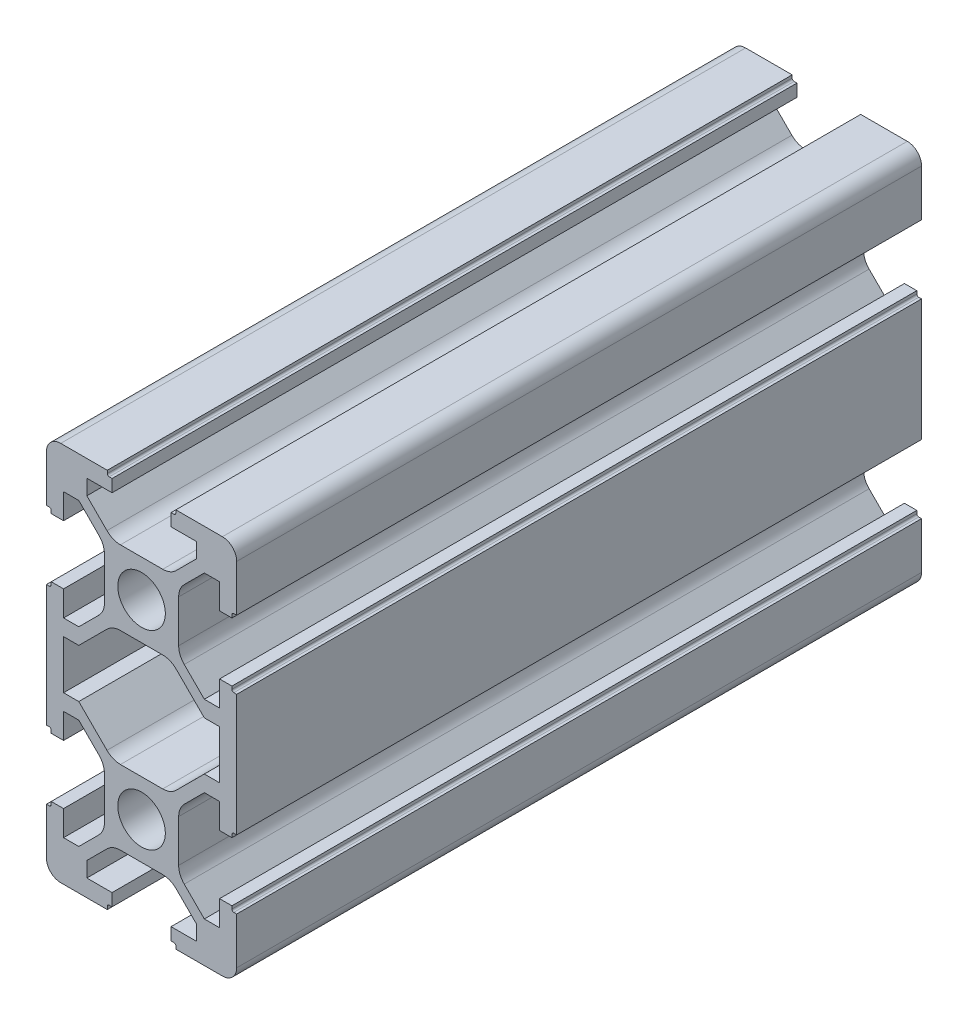
SolidWorks part; units mm, degrees
ref_plane "Alzado" through (0, 0, 0) normal (0, 0, 1) x (1, 0, 0)
ref_plane "Planta" through (0, 0, 0) normal (0, 1, 0) x (1, 0, 0)
ref_plane "Vista lateral" through (0, 0, 0) normal (1, 0, 0) x (0, 0, -1)
sketch "Croquis1" plane through (0, 0, 0) normal (0, 0, 1) x (1, 0, 0)
  line L0 (0, 0) -> (-10, -10) construction
  line L32 (0, 0) -> (-3.9, 0) construction
  line L58 (0, 0) -> (0, -3.9) construction
  line L60 (-4.4858, -3.6373) -> (-6.6, -5.7515)
  line L61 (-6.6, -5.7515) -> (-8.2, -5.7515)
  line L110 (-8.2, -5.7515) -> (-8.2, -3.1)
  line L111 (-8.2, -3.1) -> (-9.5, -3.1)
  line L112 (-9.5, -3.1) -> (-9.5, -3.4)
  line L113 (-9.7, -3.6) -> (-10, -3.6)
  line L114 (-10, -3.6) -> (-10, -8.5)
  line L115 (-3.6373, -4.4858) -> (-5.7515, -6.6)
  line L116 (-5.7515, -6.6) -> (-5.7515, -8.2)
  line L117 (-3.1, -8.2) -> (-3.1, -9.5)
  line L118 (-5.7515, -8.2) -> (-3.1, -8.2)
  line L119 (-3.1, -9.5) -> (-3.4, -9.5)
  line L120 (-3.6, -9.7) -> (-3.6, -10)
  line L121 (-3.6, -10) -> (-8.5, -10)
  line L122 (9.7, -3.6) -> (10, -3.6)
  line L123 (9.5, -3.1) -> (9.5, -3.4)
  line L124 (8.2, -3.1) -> (9.5, -3.1)
  line L125 (3.6, -10) -> (8.5, -10)
  line L126 (3.6, -9.7) -> (3.6, -10)
  line L127 (3.1, -9.5) -> (3.4, -9.5)
  line L128 (5.7515, -8.2) -> (3.1, -8.2)
  line L129 (3.1, -8.2) -> (3.1, -9.5)
  line L130 (5.7515, -6.6) -> (5.7515, -8.2)
  line L131 (3.6373, -4.4858) -> (5.7515, -6.6)
  line L132 (10, -3.6) -> (10, -8.5)
  line L133 (8.2, -5.7515) -> (8.2, -3.1)
  line L134 (6.6, -5.7515) -> (8.2, -5.7515)
  line L135 (4.4858, -3.6373) -> (6.6, -5.7515)
  line L136 (5.7515, 8.2) -> (3.1, 8.2)
  line L137 (3.6, 10) -> (8.5, 10)
  line L138 (-9.7, 3.6) -> (-10, 3.6)
  line L139 (-9.5, 3.1) -> (-9.5, 3.4)
  line L140 (-8.2, 3.1) -> (-9.5, 3.1)
  line L141 (-8.2, 5.7515) -> (-8.2, 3.1)
  line L142 (-6.6, 5.7515) -> (-8.2, 5.7515)
  line L143 (-4.4858, 3.6373) -> (-6.6, 5.7515)
  line L144 (3.1, 8.2) -> (3.1, 9.5)
  line L145 (3.1, 9.5) -> (3.4, 9.5)
  line L146 (3.6, 9.7) -> (3.6, 10)
  line L147 (-3.6, 10) -> (-8.5, 10)
  line L148 (-3.6, 9.7) -> (-3.6, 10)
  line L149 (-3.1, 9.5) -> (-3.4, 9.5)
  line L150 (-5.7515, 8.2) -> (-3.1, 8.2)
  line L151 (-3.1, 8.2) -> (-3.1, 9.5)
  line L152 (-5.7515, 6.6) -> (-5.7515, 8.2)
  line L153 (-3.6373, 4.4858) -> (-5.7515, 6.6)
  line L154 (-10, 3.6) -> (-10, 8.5)
  line L155 (4.4858, 3.6373) -> (6.6, 5.7515)
  line L156 (6.6, 5.7515) -> (8.2, 5.7515)
  line L157 (8.2, 5.7515) -> (8.2, 3.1)
  line L158 (10, 3.6) -> (10, 8.5)
  line L159 (3.6373, 4.4858) -> (5.7515, 6.6)
  line L160 (5.7515, 6.6) -> (5.7515, 8.2)
  line L161 (8.2, 3.1) -> (9.5, 3.1)
  line L162 (9.5, 3.1) -> (9.5, 3.4)
  line L163 (9.7, 3.6) -> (10, 3.6)
  line L164 (-3.9, 2.223) -> (-3.9, -2.223)
  line L165 (-2.223, -3.9) -> (2.223, -3.9)
  line L166 (3.9, -2.223) -> (3.9, 2.223)
  line L167 (2.223, 3.9) -> (-2.223, 3.9)
  circle A2 centre (0, 0) radius 2.5
  arc A3 (8.5, -10) -> (10, -8.5) centre (8.5, -8.5) ccw
  arc A4 (8.5, 10) -> (10, 8.5) centre (8.5, 8.5) cw
  arc A5 (-8.5, 10) -> (-10, 8.5) centre (-8.5, 8.5) ccw
  arc A6 (-10, -8.5) -> (-8.5, -10) centre (-8.5, -8.5) ccw
  arc A7 (-3.9, -2.223) -> (-4.4858, -3.6373) centre (-5.9, -2.223) cw
  arc A8 (4.4858, -3.6373) -> (3.9, -2.223) centre (5.9, -2.223) cw
  arc A9 (4.4858, 3.6373) -> (3.9, 2.223) centre (5.9, 2.223) ccw
  arc A10 (3.6373, 4.4858) -> (2.223, 3.9) centre (2.223, 5.9) cw
  arc A11 (-3.6373, 4.4858) -> (-2.223, 3.9) centre (-2.223, 5.9) ccw
  arc A12 (-4.4858, 3.6373) -> (-3.9, 2.223) centre (-5.9, 2.223) cw
  arc A13 (3.6373, -4.4858) -> (2.223, -3.9) centre (2.223, -5.9) ccw
  arc A14 (-3.6373, -4.4858) -> (-2.223, -3.9) centre (-2.223, -5.9) cw
  arc A15 (-3.4, -9.5) -> (-3.6, -9.7) centre (-3.4, -9.7) ccw
  arc A16 (3.6, -9.7) -> (3.4, -9.5) centre (3.4, -9.7) ccw
  arc A17 (9.7, -3.6) -> (9.5, -3.4) centre (9.7, -3.4) cw
  arc A18 (9.5, 3.4) -> (9.7, 3.6) centre (9.7, 3.4) cw
  arc A19 (3.4, 9.5) -> (3.6, 9.7) centre (3.4, 9.7) ccw
  arc A20 (-9.7, 3.6) -> (-9.5, 3.4) centre (-9.7, 3.4) cw
  arc A21 (-3.6, 9.7) -> (-3.4, 9.5) centre (-3.4, 9.7) ccw
  arc A22 (-9.5, -3.4) -> (-9.7, -3.6) centre (-9.7, -3.4) cw
  point P0 (0, 0)
  point P22 (10, -10)
  point P78 (10, 10)
  point P81 (-10, 10)
  point P90 (-3.9, -3.0515)
  point P93 (3.9, -3.0515)
  point P96 (3.9, 3.0515)
  point P99 (3.0515, 3.9)
  point P102 (-3.0515, 3.9)
  point P105 (-3.9, 3.0515)
  point P108 (3.0515, -3.9)
  point P111 (-3.0515, -3.9)
  point P116 (-3.6, -9.5)
  point P119 (3.6, -9.5)
  point P122 (9.5, -3.6)
  point P125 (9.5, 3.6)
  point P128 (3.6, 9.5)
  point P131 (-9.5, 3.6)
  point P134 (-3.6, 9.5)
  point P137 (-9.5, -3.6)
  dimension "D10" = 20
  dimension "D1" = 5
  dimension "D11" = 1.5
  dimension "D13" = 2
  dimension "D15" = 0.2
  dimension "D2" = 6.2
  dimension "D3" = 7.2
  dimension "D4" = 0.5
  dimension "D5" = 3.4
  dimension "D6" = 11.5029
  dimension "D7" = 6.1
  dimension "D8" = 1.8
  dimension "D9" = 1.2
extrude "Saliente-Extruir1" [suppressed] add sketch "Croquis1" along normal mid plane 100
sketch "Croquis3" plane through (0, 0, 0) normal (0, 0, 1) x (1, 0, 0)
  line L0 (-3.6363, -5.5152) -> (-6.6, -2.5556)
  line L3 (0, 0) -> (-10, 0) construction
  line L5 (-6.6, -2.5556) -> (-8.2, -2.5556)
  line L7 (0, -13.9) -> (0, -6.1) construction
  line L56 (-9.5, -13.1015) -> (-9.5, -13.4015)
  line L57 (-8.2, -13.1015) -> (-9.5, -13.1015)
  line L58 (-8.2, -15.7515) -> (-8.2, -13.1015)
  line L59 (-6.6, -15.7515) -> (-8.2, -15.7515)
  line L60 (-4.4858, -13.6373) -> (-6.6, -15.7515)
  line L61 (-3.9, -7.777) -> (-3.9, -12.223)
  line L62 (-6.6, -4.2515) -> (-4.4868, -6.3618)
  line L63 (-8.2, -4.2515) -> (-6.6, -4.2515)
  line L64 (-8.2, -6.9015) -> (-8.2, -4.2515)
  line L65 (-9.5, -6.9015) -> (-8.2, -6.9015)
  line L66 (-9.5, -6.6015) -> (-9.5, -6.9015)
  line L67 (-10, -6.4015) -> (-9.7, -6.4015)
  line L68 (-5.7515, -16.6) -> (-3.6373, -14.4858)
  line L69 (-5.7515, -18.2) -> (-5.7515, -16.6)
  line L70 (-3.1015, -18.2) -> (-5.7515, -18.2)
  line L71 (-3.1015, -19.5) -> (-3.1015, -18.2)
  line L72 (-3.4015, -19.5) -> (-3.1015, -19.5)
  line L73 (-3.6015, -20) -> (-3.6015, -19.7)
  line L74 (-8.5, -20) -> (-3.6015, -20)
  line L75 (-10, -13.6015) -> (-10, -18.5)
  line L76 (-9.7, -13.6015) -> (-10, -13.6015)
  line L102 (-10, -6.4015) -> (-10, 6.4015)
  line L103 (-8.2, -2.5556) -> (-8.2, 2.5556)
  line L104 (-2.223, -6.1) -> (2.223, -6.1)
  line L105 (-2.223, -13.9) -> (2.223, -13.9)
  line L106 (8.2, -2.5556) -> (8.2, 2.5556)
  line L107 (10, -6.4015) -> (10, 6.4015)
  line L108 (9.7, -13.6015) -> (10, -13.6015)
  line L109 (10, -13.6015) -> (10, -18.5)
  line L110 (8.5, -20) -> (3.6015, -20)
  line L111 (3.6015, -20) -> (3.6015, -19.7)
  line L112 (3.4015, -19.5) -> (3.1015, -19.5)
  line L113 (3.1015, -19.5) -> (3.1015, -18.2)
  line L114 (3.1015, -18.2) -> (5.7515, -18.2)
  line L115 (5.7515, -18.2) -> (5.7515, -16.6)
  line L116 (5.7515, -16.6) -> (3.6373, -14.4858)
  line L117 (10, -6.4015) -> (9.7, -6.4015)
  line L118 (9.5, -6.6015) -> (9.5, -6.9015)
  line L119 (9.5, -6.9015) -> (8.2, -6.9015)
  line L120 (8.2, -6.9015) -> (8.2, -4.2515)
  line L121 (8.2, -4.2515) -> (6.6, -4.2515)
  line L122 (6.6, -4.2515) -> (4.4868, -6.3618)
  line L123 (3.9, -7.777) -> (3.9, -12.223)
  line L124 (4.4858, -13.6373) -> (6.6, -15.7515)
  line L125 (6.6, -15.7515) -> (8.2, -15.7515)
  line L126 (8.2, -15.7515) -> (8.2, -13.1015)
  line L127 (8.2, -13.1015) -> (9.5, -13.1015)
  line L128 (9.5, -13.1015) -> (9.5, -13.4015)
  line L129 (6.6, -2.5556) -> (8.2, -2.5556)
  line L130 (3.6363, -5.5152) -> (6.6, -2.5556)
  line L131 (3.6363, 5.5152) -> (6.6, 2.5556)
  line L132 (6.6, 2.5556) -> (8.2, 2.5556)
  line L133 (9.5, 13.1015) -> (9.5, 13.4015)
  line L134 (8.2, 13.1015) -> (9.5, 13.1015)
  line L135 (8.2, 15.7515) -> (8.2, 13.1015)
  line L136 (6.6, 15.7515) -> (8.2, 15.7515)
  line L137 (4.4858, 13.6373) -> (6.6, 15.7515)
  line L138 (3.9, 7.777) -> (3.9, 12.223)
  line L139 (6.6, 4.2515) -> (4.4868, 6.3618)
  line L140 (8.2, 4.2515) -> (6.6, 4.2515)
  line L141 (8.2, 6.9015) -> (8.2, 4.2515)
  line L142 (9.5, 6.9015) -> (8.2, 6.9015)
  line L143 (9.5, 6.6015) -> (9.5, 6.9015)
  line L144 (10, 6.4015) -> (9.7, 6.4015)
  line L145 (5.7515, 16.6) -> (3.6373, 14.4858)
  line L146 (5.7515, 18.2) -> (5.7515, 16.6)
  line L147 (3.1015, 18.2) -> (5.7515, 18.2)
  line L148 (3.1015, 19.5) -> (3.1015, 18.2)
  line L149 (3.4015, 19.5) -> (3.1015, 19.5)
  line L150 (3.6015, 20) -> (3.6015, 19.7)
  line L151 (8.5, 20) -> (3.6015, 20)
  line L152 (10, 13.6015) -> (10, 18.5)
  line L153 (9.7, 13.6015) -> (10, 13.6015)
  line L154 (-2.223, 13.9) -> (2.223, 13.9)
  line L155 (-2.223, 6.1) -> (2.223, 6.1)
  line L156 (-9.7, 13.6015) -> (-10, 13.6015)
  line L157 (-10, 13.6015) -> (-10, 18.5)
  line L158 (-8.5, 20) -> (-3.6015, 20)
  line L159 (-3.6015, 20) -> (-3.6015, 19.7)
  line L160 (-3.4015, 19.5) -> (-3.1015, 19.5)
  line L161 (-3.1015, 19.5) -> (-3.1015, 18.2)
  line L162 (-3.1015, 18.2) -> (-5.7515, 18.2)
  line L163 (-5.7515, 18.2) -> (-5.7515, 16.6)
  line L164 (-5.7515, 16.6) -> (-3.6373, 14.4858)
  line L165 (-10, 6.4015) -> (-9.7, 6.4015)
  line L166 (-9.5, 6.6015) -> (-9.5, 6.9015)
  line L167 (-9.5, 6.9015) -> (-8.2, 6.9015)
  line L168 (-8.2, 6.9015) -> (-8.2, 4.2515)
  line L169 (-8.2, 4.2515) -> (-6.6, 4.2515)
  line L170 (-6.6, 4.2515) -> (-4.4868, 6.3618)
  line L171 (-3.9, 7.777) -> (-3.9, 12.223)
  line L172 (-4.4858, 13.6373) -> (-6.6, 15.7515)
  line L173 (-6.6, 15.7515) -> (-8.2, 15.7515)
  line L174 (-8.2, 15.7515) -> (-8.2, 13.1015)
  line L175 (-8.2, 13.1015) -> (-9.5, 13.1015)
  line L176 (-9.5, 13.1015) -> (-9.5, 13.4015)
  line L177 (-6.6, 2.5556) -> (-8.2, 2.5556)
  line L178 (-3.6363, 5.5152) -> (-6.6, 2.5556)
  line L179 (0, -10) -> (-9.5607, -19.5607) construction
  circle A8 centre (0, -10) radius 2.5
  arc A20 (-4.4858, -13.6373) -> (-3.9, -12.223) centre (-5.9, -12.223) ccw
  arc A21 (-3.9, -7.777) -> (-4.4868, -6.3618) centre (-5.9, -7.777) ccw
  arc A22 (-9.5, -6.6015) -> (-9.7, -6.4015) centre (-9.7, -6.6015) ccw
  arc A23 (-3.6363, -5.5152) -> (-2.223, -6.1) centre (-2.223, -4.1) ccw
  arc A24 (-2.223, -13.9) -> (-3.6373, -14.4858) centre (-2.223, -15.9) ccw
  arc A25 (-3.4015, -19.5) -> (-3.6015, -19.7) centre (-3.4015, -19.7) ccw
  arc A26 (-10, -18.5) -> (-8.5, -20) centre (-8.5, -18.5) ccw
  arc A27 (-9.7, -13.6015) -> (-9.5, -13.4015) centre (-9.7, -13.4015) ccw
  arc A34 (9.7, -13.6015) -> (9.5, -13.4015) centre (9.7, -13.4015) cw
  arc A35 (10, -18.5) -> (8.5, -20) centre (8.5, -18.5) cw
  arc A36 (3.4015, -19.5) -> (3.6015, -19.7) centre (3.4015, -19.7) cw
  arc A37 (2.223, -13.9) -> (3.6373, -14.4858) centre (2.223, -15.9) cw
  arc A38 (3.6363, -5.5152) -> (2.223, -6.1) centre (2.223, -4.1) cw
  arc A39 (9.5, -6.6015) -> (9.7, -6.4015) centre (9.7, -6.6015) cw
  arc A40 (3.9, -7.777) -> (4.4868, -6.3618) centre (5.9, -7.777) cw
  arc A41 (4.4858, -13.6373) -> (3.9, -12.223) centre (5.9, -12.223) cw
  arc A42 (4.4858, 13.6373) -> (3.9, 12.223) centre (5.9, 12.223) ccw
  arc A43 (3.9, 7.777) -> (4.4868, 6.3618) centre (5.9, 7.777) ccw
  arc A44 (9.5, 6.6015) -> (9.7, 6.4015) centre (9.7, 6.6015) ccw
  arc A45 (3.6363, 5.5152) -> (2.223, 6.1) centre (2.223, 4.1) ccw
  arc A46 (2.223, 13.9) -> (3.6373, 14.4858) centre (2.223, 15.9) ccw
  arc A47 (3.4015, 19.5) -> (3.6015, 19.7) centre (3.4015, 19.7) ccw
  arc A48 (10, 18.5) -> (8.5, 20) centre (8.5, 18.5) ccw
  arc A49 (9.7, 13.6015) -> (9.5, 13.4015) centre (9.7, 13.4015) ccw
  arc A50 (-9.7, 13.6015) -> (-9.5, 13.4015) centre (-9.7, 13.4015) cw
  arc A51 (-10, 18.5) -> (-8.5, 20) centre (-8.5, 18.5) cw
  arc A52 (-3.4015, 19.5) -> (-3.6015, 19.7) centre (-3.4015, 19.7) cw
  arc A53 (-2.223, 13.9) -> (-3.6373, 14.4858) centre (-2.223, 15.9) cw
  arc A54 (-3.6363, 5.5152) -> (-2.223, 6.1) centre (-2.223, 4.1) cw
  arc A55 (-9.5, 6.6015) -> (-9.7, 6.4015) centre (-9.7, 6.6015) cw
  arc A56 (-3.9, 7.777) -> (-4.4868, 6.3618) centre (-5.9, 7.777) cw
  arc A57 (-4.4858, 13.6373) -> (-3.9, 12.223) centre (-5.9, 12.223) cw
  circle A58 centre (0, 10) radius 2.5
  point P59 (8.2, 0)
  point P63 (8.2, 0)
  point P159 (10, 0)
  point P160 (-8.2, 0)
  point P174 (-8.2, 0)
  point P190 (-3.9, -10)
  point P193 (0, -10)
  dimension "D8" = 2
  dimension "D9" = 1.5
  dimension "D11" = 5
  dimension "D13" = 0.2
  dimension "D1" = 40
  dimension "D2" = 11.5
  dimension "D3" = 6.2
  dimension "D4" = 1.8
  dimension "D5" = 0.5
  dimension "D6" = 3.4
  dimension "D7" = 20
  dimension "D10" = 1.2
  dimension "D12" = 7.8
  dimension "D14" = 20
extrude "Saliente-Extruir3" add sketch "Croquis3" along normal mid plane 350 separate body
sketch "Sketch1" plane through (0, 20, 0) normal (0, 1, 0) x (1, 0, 0)
  line L0 (10, 175) -> (8.5, 175) construction
  line L1 (8.5, -175) -> (10, -175) construction
  line L2 (10, -175) -> (10, 175) construction
  line L3 (8.5, 175) -> (3.6015, 175) construction
  line L4 (3.6015, 175) -> (3.6015, -175) construction
  line L5 (3.6015, -175) -> (8.5, -175) construction
  line L6 (3.6373, 175) -> (2.223, 175) construction
  line L7 (2.223, -175) -> (3.6373, -175) construction
  line L8 (3.6373, -175) -> (3.6373, 175) construction
  line L10 (-2.223, -175) -> (2.223, -175) construction
  line L11 (-2.223, 175) -> (-3.6373, 175) construction
  line L12 (-3.6373, 175) -> (-3.6373, -175) construction
  line L13 (-3.6373, -175) -> (-2.223, -175) construction
  line L14 (-3.6015, 175) -> (-8.5, 175) construction
  line L15 (-8.5, -175) -> (-3.6015, -175) construction
  line L16 (-3.6015, -175) -> (-3.6015, 175) construction
  line L17 (-8.5, 175) -> (-10, 175) construction
  line L18 (-10, 175) -> (-10, -175) construction
  line L19 (-10, -175) -> (-8.5, -175) construction
  line L20 (10, 175) -> (8.5, 175)
  line L21 (8.5, -175) -> (10, -175)
  line L22 (10, -175) -> (10, 103)
  line L23 (3.6373, 175) -> (3.6015, 175)
  line L24 (3.6015, 103) -> (3.6015, -175)
  line L25 (3.6015, -175) -> (8.5, -175)
  line L26 (3.6373, 175) -> (2.223, 175)
  line L27 (2.223, -175) -> (3.6373, -175)
  line L28 (3.6373, -175) -> (3.6373, 103)
  line L30 (-2.223, -175) -> (2.223, -175)
  line L31 (-3.6015, 175) -> (-3.6373, 175)
  line L32 (-3.6373, 103) -> (-3.6373, -175)
  line L33 (-3.6373, -175) -> (-2.223, -175)
  line L34 (-3.6015, 175) -> (-3.6373, 175)
  line L35 (-8.5, -175) -> (-3.6015, -175)
  line L36 (-3.6015, -175) -> (-3.6015, 103)
  line L37 (-8.5, 175) -> (-10, 175)
  line L38 (-10, 103) -> (-10, -175)
  line L39 (-10, -175) -> (-8.5, -175)
  line L40 (-10, 103) -> (10, 103)
  line L41 (10, 103) -> (10, -175)
  line L42 (10, -175) -> (8.5, -175)
  line L43 (10, -175) -> (-10, -175)
  line L44 (-10, -175) -> (-10, 103)
  line M6 (-8.5, 175) -> (-8.5, -175)
  line M7 (-8.5, -175) -> (-3.6015, -175)
  line M8 (-3.6015, -175) -> (-3.6015, 175)
  dimension "D1" = 350
  dimension "D2" = 278
extrude "Cut-Extrude3" cut sketch "Sketch1" against normal blind 100 contours L40 L28 L25 L21 L22 | L40 L33 L30 L27 L24 M8 | L40 L32 M6 M7 | L40 L38 L39 M6 | L40 L32 M7 M8 | L40 L24 L25 L28
sketch "Sketch2" plane through (10, 0, 0) normal (1, 0, 0) x (0, 0, -1)
  line L8 (103, 6.4015) -> (103, -6.4015) construction
  line L9 (103, -6.4015) -> (175, -6.4015) construction
  line L10 (175, -6.4015) -> (175, 6.4015) construction
  line L11 (175, 6.4015) -> (103, 6.4015) construction
  line L12 (103, 20) -> (103, 18.5)
  line L14 (175, 18.5) -> (175, 20)
  line L16 (103, -18.5) -> (103, -20)
  line L18 (175, -20) -> (175, -18.5)
  line L20 (103, 6.4015) -> (103, -6.4015)
  line L21 (103, -6.4015) -> (175, -6.4015)
  line L22 (175, -6.4015) -> (175, 6.4015)
  line L23 (175, 6.4015) -> (103, 6.4015)
  line L24 (103, 18.5) -> (103, -18.2)
  line L25 (175, 18.5) -> (175, -18.5)
  line L26 (125, 20) -> (125, -20)
  line L27 (125, 0) -> (175, 0) construction
  line L28 (125, -20) -> (175, -20)
  line L29 (150, 20) -> (150, -20) construction
  line L30 (103, 18.5) -> (175, 18.5) construction
  line L31 (103, 20) -> (175, 20) construction
  line L32 (103, 18.5) -> (175, 18.5)
  line L33 (103, 20) -> (175, 20)
  line L34 (103, -20) -> (175, -20) construction
  line L35 (103, -18.5) -> (175, -18.5) construction
  line L36 (103, -20) -> (175, -20)
  line L37 (103, -18.5) -> (175, -18.5)
  circle A0 centre (137.5, 10) radius 3
  circle A1 centre (162.5, 10) radius 3
  circle A2 centre (162.5, -10) radius 3
  circle A3 centre (137.5, -10) radius 3
  point P21 (137.5, 10)
  point P23 (162.5, 10)
  point P25 (162.5, -10)
  point P27 (137.5, -10)
  dimension "D3" = 6
  dimension "D1" = 50
  dimension "D2" = 25
  dimension "D5" = 12.5
  dimension "D6" = 72
hole_wizard "Ø6.0mm Dowel Hole1" [suppressed] positions "Sketch2" profile "Sketch4" hole size "Ø6.0" standard "ANSI Metric"
sketch "Sketch4" plane through (10, -10, -137.5) normal (0, 1, 0) x (0, 0, -1)
  line L0 (0, 0) -> (0, 20)
  line L1 (0, 20) -> (3, 20)
  line L2 (3, 20) -> (3, 0)
  line L5 (3, 0) -> (0, 0)
  line L11 (0, -6.35) -> (0, 107.95) construction
  dimension "Thru Hole Dia." = 6
  dimension "Thru Hole Depth" = 20
